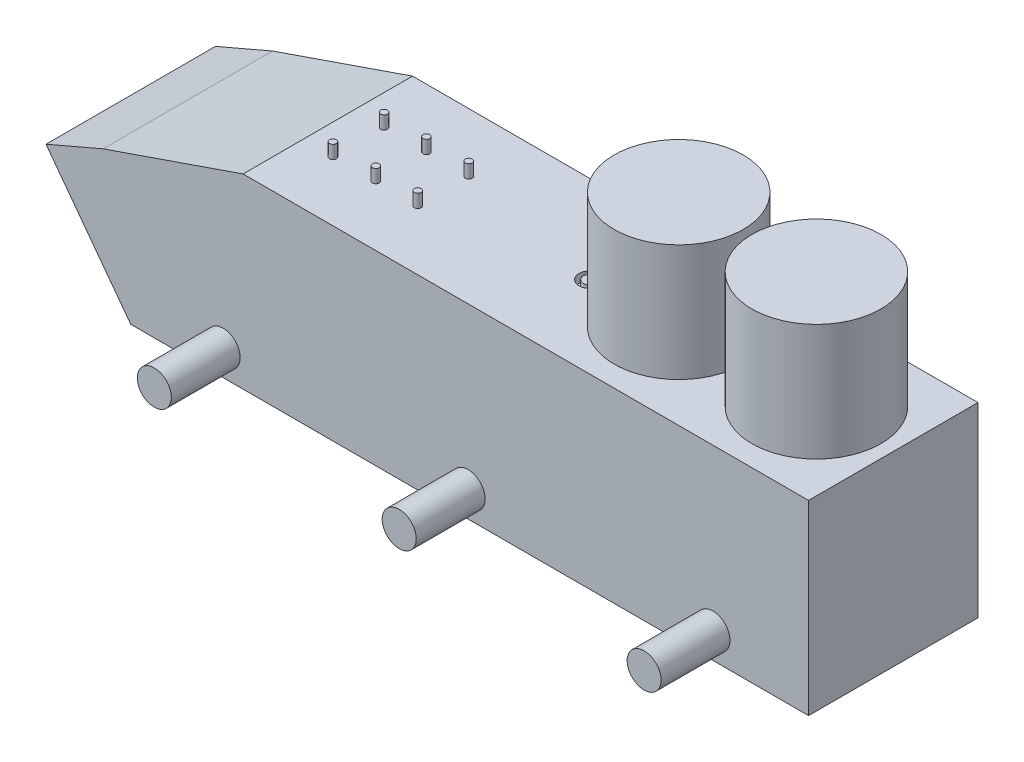
SolidWorks part; units mm, degrees
ref_plane "Front Plane" through (0, 0, 0) normal (0, 0, 1) x (1, 0, 0)
ref_plane "Top Plane" through (0, 0, 0) normal (0, 1, 0) x (1, 0, 0)
ref_plane "Right Plane" through (0, 0, 0) normal (1, 0, 0) x (0, 0, -1)
sketch "Sketch2" plane through (0, 0, 0) normal (0, 0, 1) x (1, 0, 0)
  line L0 (-600, 76.0791) -> (-100, 290.8273)
  line L1 (1650, -259.1727) -> (-350, -259.1727)
  line L2 (1650, -259.1727) -> (1650, 290.8273)
  line L3 (1650, 290.8273) -> (-100, 290.8273)
  line L5 (-600, 76.0791) -> (-350, -259.1727)
  point P0 (0, 0)
  dimension "D1" = 2000
extrude "Boss-Extrude1" add sketch "Sketch2" along normal blind 500
sketch "Sketch3" plane through (0, 0, 0) normal (0, 0, 1) x (1, 0, 0)
  line L0 (-629.1602, 80.3183) -> (0, 297.1977)
  line L1 (0, 297.1977) -> (-133.9456, 297.1977)
  line L2 (-133.9456, 297.1977) -> (-629.1602, 80.3183)
extrude "Cut-Extrude2" cut sketch "Sketch3" along normal through all both and the other way through all
sketch "Sketch9" plane through (0, 0, 0) normal (0, 1, 0) x (1, 0, 0)
  line L0 (1421.4, -248.1493) -> (1015, -248.1493)
  line L1 (1015, -248.1493) -> (409.1563, -248.1493)
  line L2 (1650, -500) -> (1650, 0) construction
  circle A0 centre (1421.4, -248.1493) radius 190.5
  circle A2 centre (1015, -248.1493) radius 190.5
  dimension "D1" = 381
  dimension "D2" = 381
  dimension "D5" = 228.6
  dimension "D3" = 406.4
  dimension "D4" = 406.4
sketch "Sketch11" plane through (0, 0, 0) normal (0, 1, 0) x (1, 0, 0)
  circle A2 centre (320.5936, -323.7889) radius 10
  circle A3 centre (70.5936, -323.7889) radius 10
  circle A5 centre (195.5936, -322.3262) radius 10
  circle A6 centre (195.5936, -322.3262) radius 10
  circle A7 centre (320.5936, -173.1256) radius 10
  circle A8 centre (195.5936, -173.1256) radius 10
  circle A9 centre (70.5936, -173.1256) radius 10
extrude "Boss-Extrude8" add sketch "Sketch11" along normal blind 330 contours A9 | A8 | A7 | A2 | A5 | A3
sketch "Sketch12" plane through (0, 0, 0) normal (0, 0, -1) x (-1, 0, 0)
  line L0 (-1650, -259.1727) -> (-1650, 290.8273) construction
  line L1 (350, -259.1727) -> (-1650, -259.1727) construction
  circle A0 centre (-1345.2, -182.9727) radius 50.165
  circle A1 centre (77.2, -182.9727) radius 50.165
  dimension "D1" = 100.33
  dimension "D3" = 100.33
  dimension "D2" = 304.8
  dimension "D4" = 1422.4
  dimension "D5" = 76.2
  dimension "D6" = 76.2
extrude "Boss-Extrude14" add sketch "Sketch12" along normal blind 203.2
sketch "Sketch15" plane through (0, 0, 500) normal (0, 0, 1) x (1, 0, 0)
  line L0 (1650, -259.1727) -> (1650, 290.8273) construction
  line L1 (-350, -259.1727) -> (1650, -259.1727) construction
  circle A0 centre (1368.06, -182.9727) radius 50.165
  circle A1 centre (-77.2, -182.9727) radius 50.165
  dimension "D1" = 100.33
  dimension "D4" = 100.33
  dimension "D2" = 281.94
  dimension "D3" = 76.2
  dimension "D5" = 1445.26
extrude "Boss-Extrude15" add sketch "Sketch15" along normal blind 203.2
sketch "Sketch17" plane through (0, 0, 500) normal (0, 0, 1) x (1, 0, 0)
  line L0 (-350, -259.1727) -> (1650, -259.1727) construction
  circle A0 centre (645.43, -182.9727) radius 50.292
  circle A1 centre (-77.2, -182.9727) radius 50.165 construction
  dimension "D1" = 100.584
  dimension "D3" = 722.63
  dimension "D2" = 76.2
extrude "Boss-Extrude16" add sketch "Sketch17" along normal through all
sketch "Sketch18" plane through (0, 0, 0) normal (0, 0, -1) x (-1, 0, 0)
  line L0 (350, -259.1727) -> (-1650, -259.1727) construction
  circle A0 centre (-622.57, -182.9727) radius 50.165
  circle A1 centre (-1345.2, -182.9727) radius 50.165 construction
  dimension "D1" = 100.33
  dimension "D3" = 722.63
  dimension "D2" = 76.2
extrude "Boss-Extrude17" add sketch "Sketch18" along normal through all
extrude "Boss-Extrude19" add sketch "Sketch9" along normal blind 635 contours A2 | A0
sketch "Sketch19" plane through (0, 290.8273, 0) normal (0, 1, 0) x (1, 0, 0)
  circle A0 centre (763.2206, -258.5396) radius 19.05
  circle A1 centre (763.2206, -258.5396) radius 31.75
  dimension "D1" = 38.1
  dimension "D2" = 63.5
extrude "Cut-Extrude5" cut sketch "Sketch19" against normal blind 25.4
